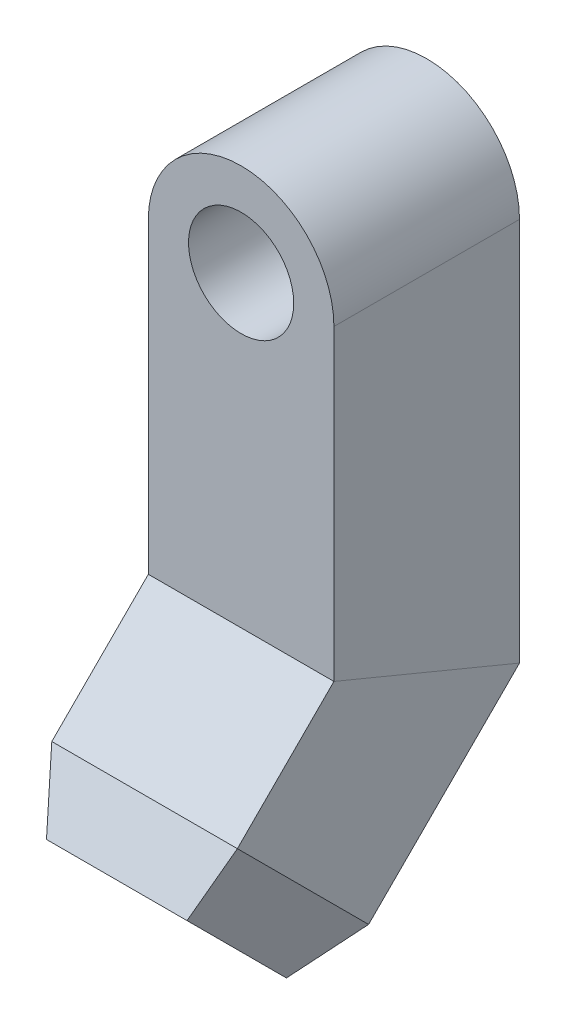
SolidWorks part; units mm, degrees
ref_plane "Front Plane" through (0, 0, 0) normal (0, 0, 1) x (1, 0, 0)
ref_plane "Top Plane" through (0, 0, 0) normal (0, 1, 0) x (1, 0, 0)
ref_plane "Right Plane" through (0, 0, 0) normal (1, 0, 0) x (0, 0, -1)
ref_plane "Plane2" through (0, 96.393, 0) normal (0, 1, 0) x (1, 0, 0)
sketch "Sketch10" plane through (0, 0, 0) normal (1, 0, 0) x (0, 0, -1)
  line L0 (0, 96.393) -> (0, 25.4)
  line L1 (55, 96.393) -> (-55, 96.393) construction
  line L2 (0, 25.4) -> (-25.4, 0)
  line L3 (55, 0) -> (-55, 0) construction
  dimension "D1" = 70.993
  dimension "D2" = 135
sketch "Sketch11" plane through (0, 96.393, 0) normal (0, 1, 0) x (1, 0, 0)
  line L1 (-19.05, -19.05) -> (19.05, -19.05)
  line L2 (-19.05, -19.05) -> (-19.05, 19.05)
  line L3 (-19.05, 19.05) -> (19.05, 19.05)
  line L4 (19.05, -19.05) -> (19.05, 19.05)
  line L5 (-19.05, -19.05) -> (19.05, 19.05) construction
  line L6 (-19.05, 19.05) -> (19.05, -19.05) construction
  point P0 (0, 0)
  dimension "D1" = 38.1
sweep "Sweep1" add profiles "Sketch11" path "Sketch10"
sketch "Sketch12" plane through (0, -12.7, 12.7) normal (0, -0.7071, 0.7071) x (1, 0, 0)
  line L8 (19.05, -1.0895) -> (19.05, 37.0105)
  line L9 (19.05, 37.0105) -> (-19.05, 37.0105)
  line L10 (-19.05, 37.0105) -> (-19.05, -1.0895)
  line L11 (-19.05, -1.0895) -> (19.05, -1.0895)
  line L12 (19.05, -1.0895) -> (19.05, 37.0105)
  line L13 (19.05, 37.0105) -> (-19.05, 37.0105)
  line L14 (-19.05, 37.0105) -> (-19.05, -1.0895)
  line L15 (-19.05, -1.0895) -> (19.05, -1.0895)
  dimension "D1" = 0
extrude "Boss-Extrude5" add sketch "Sketch12" along normal blind 12.7 draft 20
sketch "Sketch13" plane through (0, 0, -19.05) normal (0, 0, -1) x (-1, 0, 0)
  line L0 (55, 96.393) -> (-55, 96.393) construction
  line L1 (0, 55) -> (0, -55) construction
  line L2 (-19.05, 96.393) -> (19.05, 96.393)
  arc A0 (19.05, 96.393) -> (-19.05, 96.393) centre (0, 96.393) ccw
  dimension "D1" = 38.1
extrude "Boss-Extrude6" add sketch "Sketch13" against normal up to surface (38.1 mm away) up to face at (0, 64.8419, 19.05)
sketch "Sketch14" plane through (0, 0, 19.05) normal (0, 0, 1) x (1, 0, 0)
  circle A0 centre (0, 96.393) radius 10.795
  arc A1 (19.05, 96.393) -> (-19.05, 96.393) centre (0, 96.393) ccw construction
  dimension "D1" = 21.59
extrude "Cut-Extrude2" cut sketch "Sketch14" against normal blind 38.1
sketch "Sketch15" plane through (0, -21.6803, 21.6803) normal (0, -0.7071, 0.7071) x (1, 0, 0)
  line L0 (0, -34.9977) -> (0, 34.9977) construction
  line L4 (-14.4276, 32.3881) -> (-14.4276, 3.5329) construction
  line L5 (-14.4276, 3.5329) -> (14.4276, 3.5329) construction
  line L8 (0, 32.3881) -> (0, 3.5329) construction
  line L9 (14.4276, 32.3881) -> (-14.4276, 32.3881) construction
  circle A0 centre (0, 17.9605) radius 10.795
  point P12 (-14.4276, 17.9605)
  dimension "D1" = 21.59
extrude "Cut-Extrude3" cut sketch "Sketch15" against normal blind 12.7
